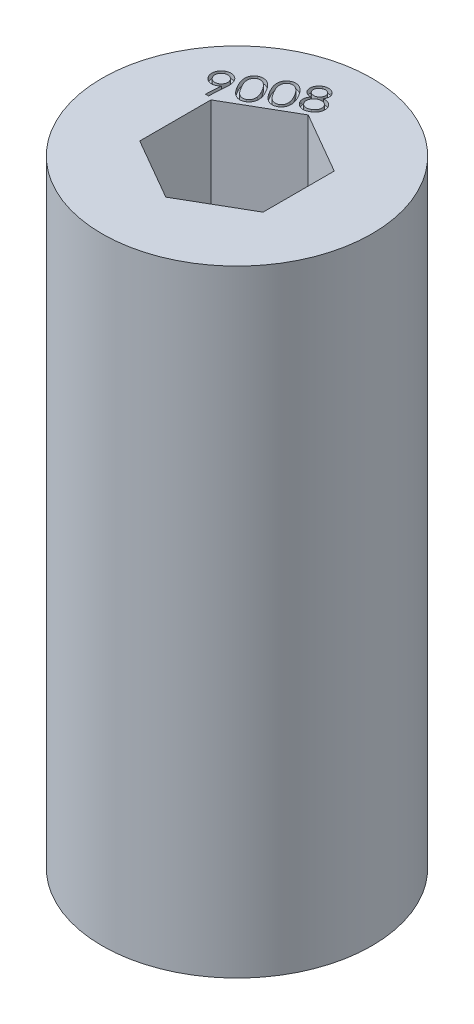
SolidWorks part; units mm, degrees
material "ABS"
ref_plane "Front Plane" through (0, 0, 0) normal (0, 0, 1) x (1, 0, 0)
ref_plane "Top Plane" through (0, 0, 0) normal (0, 1, 0) x (1, 0, 0)
ref_plane "Right Plane" through (0, 0, 0) normal (1, 0, 0) x (0, 0, -1)
sketch "Sketch1" plane through (0, 0, 0) normal (0, 1, 0) x (1, 0, 0)
  line L1 (0, 5.8659) -> (-5.08, 2.9329)
  line L2 (-5.08, 2.9329) -> (-5.08, -2.9329)
  line L3 (-5.08, -2.9329) -> (0, -5.8659)
  line L4 (0, -5.8659) -> (5.08, -2.9329)
  line L5 (5.08, -2.9329) -> (5.08, 2.9329)
  line L6 (5.08, 2.9329) -> (0, 5.8659)
  circle A0 centre (0, 0) radius 11.1125
  circle A1 centre (0, 0) radius 5.08 construction
  dimension "D1" = 22.225
  dimension "D2" = 10.16
extrude "Boss-Extrude1" add sketch "Sketch1" along normal blind 50.8
sketch "Sketch2" plane through (0, 50.8, 0) normal (0, 1, 0) x (1, 0, 0)
  line L0 (-6.0835, 2.8229) -> (0.5692, 6.6638) construction
  line L1 (0, 5.8659) -> (-5.08, 2.9329) construction
  text T0 "9008" font "Century Gothic" height 2.54
  dimension "D1" = 0.4064
extrude "Cut-Extrude1" cut sketch "Sketch2" against normal blind 0.4
